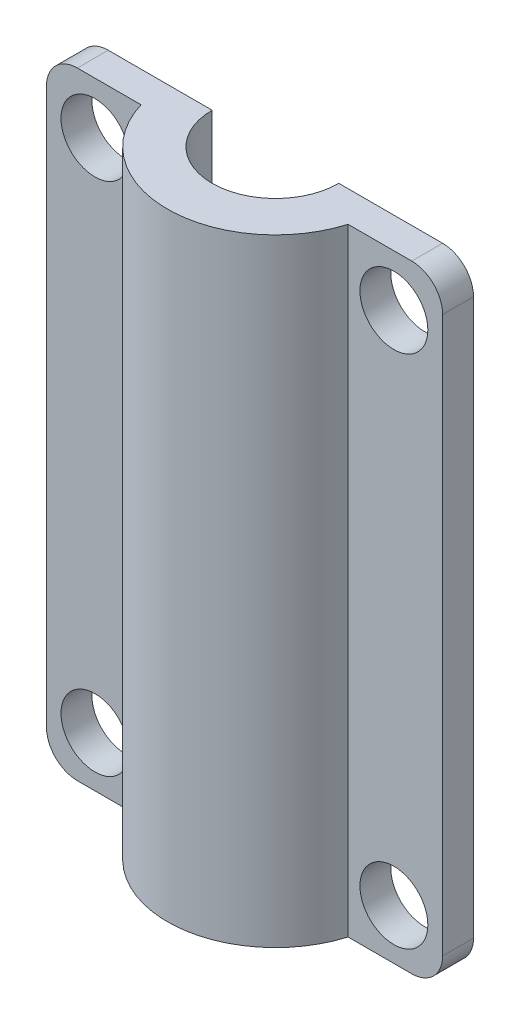
SolidWorks part; units mm, degrees
ref_plane "前视基准面" through (0, 0, 0) normal (0, 0, 1) x (1, 0, 0)
ref_plane "上视基准面" through (0, 0, 0) normal (0, 1, 0) x (1, 0, 0)
ref_plane "右视基准面" through (0, 0, 0) normal (1, 0, 0) x (0, 0, -1)
sketch "草图1" plane through (0, 0, 0) normal (0, 1, 0) x (1, 0, 0)
  line L0 (72.7407, -14.2872) -> (66.8654, -14.2872) construction
  line L1 (67.3512, -14.2872) -> (67.3512, -15.2872)
  line L2 (67.3512, -15.2872) -> (80.1864, -15.2872) construction
  line L3 (67.3512, -15.2872) -> (67.3512, -13.2872) construction
  line L4 (67.3512, -13.2872) -> (80.1864, -13.2872) construction
  line L5 (80.1864, -15.2872) -> (80.1864, -13.2872) construction
  line L6 (67.3512, -15.2872) -> (80.1864, -13.2872) construction
  line L7 (67.3512, -13.2872) -> (80.1864, -15.2872) construction
  line L9 (77.1229, -15.2872) -> (80.1864, -15.2872)
  line L10 (80.1864, -15.2872) -> (80.1864, -14.2872)
  line L11 (80.1864, -14.2872) -> (75.8239, -14.2872)
  line L13 (67.3512, -15.2872) -> (70.4147, -15.2872)
  line L14 (71.7188, -14.2872) -> (67.3512, -14.2872)
  circle A0 centre (73.7688, -14.2872) radius 2.05 construction
  circle A1 centre (73.7688, -14.2872) radius 3.5 construction
  arc A4 (70.4147, -15.2872) -> (77.1229, -15.2872) centre (73.7688, -14.2872) ccw
  arc A5 (71.7188, -14.2872) -> (75.8239, -14.2872) centre (73.7713, -14.2872) ccw
  dimension "D1" = 1
  dimension "D2" = 4.1
  dimension "D3" = 7
extrude "凸台-拉伸1" add sketch "草图1" along normal blind 20
sketch "草图2" plane through (0, 0, 15.2872) normal (0, 0, 1) x (1, 0, 0)
  line L2 (78.6066, 8) -> (78.6066, 7.4124) construction
  line L6 (69.1412, 9.9785) -> (70.2164, 9.9785) construction
  line L9 (68.921, 18.3273) -> (78.6066, 18.3273) construction
  line L10 (68.921, 18.3273) -> (68.921, 1.6297) construction
  line L11 (68.921, 1.6297) -> (78.6066, 1.6297) construction
  line L12 (78.6066, 18.3273) -> (78.6066, 1.6297) construction
  line L13 (68.921, 18.3273) -> (78.6066, 1.6297) construction
  line L14 (68.921, 1.6297) -> (78.6066, 18.3273) construction
  circle A0 centre (68.921, 18.3273) radius 1.1
  circle A1 centre (68.921, 1.6297) radius 1.1
  circle A2 centre (78.6066, 18.3273) radius 1.1
  circle A3 centre (78.6066, 1.6297) radius 1.1
  point P0 (69.0435, 1.3388)
  point P2 (0, 0)
  point P5 (73.7638, 9.9785)
  point P18 (0, 0)
extrude "切除-拉伸1" cut sketch "草图2" against normal through all both and the other way through all
fillet "圆角1" radius 1 4 edges at (80.1864, 20, 14.7872) (80.1864, 0, 14.7872) (67.3512, 20, 14.7872) (67.3512, 0, 14.7872)
